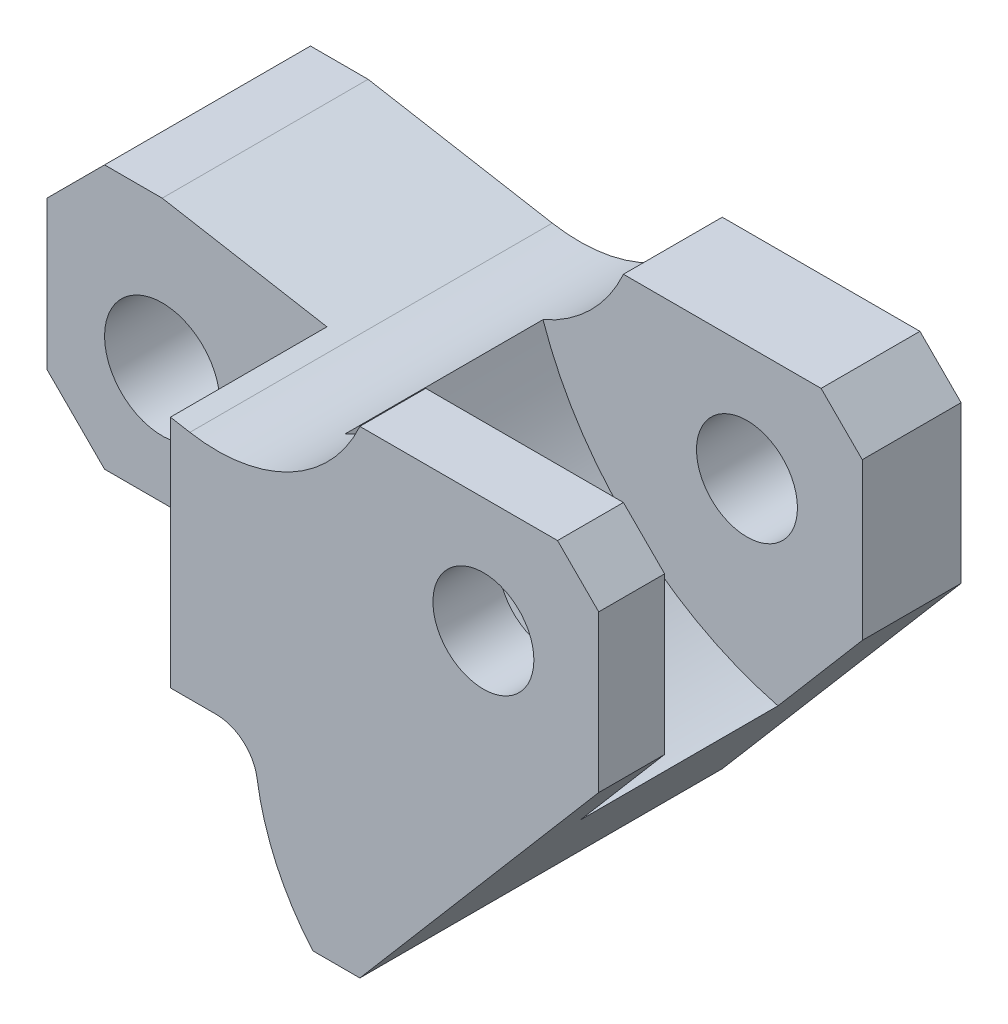
SolidWorks part; units mm, degrees
material "AISI 1020"
ref_plane "Front Plane" through (0, 0, 0) normal (0, 0, 1) x (1, 0, 0)
ref_plane "Top Plane" through (0, 0, 0) normal (0, 1, 0) x (1, 0, 0)
ref_plane "Right Plane" through (0, 0, 0) normal (1, 0, 0) x (0, 0, -1)
sketch "Sketch4" plane through (0, 0, 0) normal (0, 0, 1) x (1, 0, 0)
  line L0 (-153.4752, 21.7594) -> (-153.4752, 53.7594)
  line L1 (-153.4752, 53.7594) -> (-139.4752, 53.7594)
  line L2 (-139.4752, 53.7594) -> (-117.1138, 49.8164)
  line L3 (-96.4752, 60.7594) -> (-67.4752, 60.7594)
  line L4 (-67.4752, 60.7594) -> (-67.4752, 36.7594)
  line L5 (-67.4752, 36.7594) -> (-96.4752, 2.7594)
  line L6 (-96.4752, 2.7594) -> (-102.1782, 2.7594)
  line L7 (-153.4752, 21.7594) -> (-113.8997, 21.7594)
  arc A0 (-117.1138, 49.8164) -> (-96.4752, 60.7594) centre (-113.8145, 68.5278) ccw
  arc A1 (-102.1782, 2.7594) -> (-108.954, 17.4947) centre (-80.2693, 21.7594) cw construction
  arc A2 (-108.954, 17.4947) -> (-113.8997, 21.7594) centre (-113.8997, 16.7594) ccw construction
  arc A3 (-113.8997, 21.7594) -> (-108.954, 17.4947) centre (-113.8997, 16.7594) cw
  arc A4 (-108.954, 17.4947) -> (-102.1782, 2.7594) centre (-80.2693, 21.7594) ccw
  dimension "D4" = 19
  dimension "D9" = 29
  dimension "D10" = 5
  dimension "D1" = 32
  dimension "D2" = 14
  dimension "D3" = 10
  dimension "D5" = 29
  dimension "D6" = 24
  dimension "D7" = 29
  dimension "D8" = 58
  dimension "D11" = 19
  dimension "D12" = 86
  dimension "D13" = 19
extrude "Boss-Extrude1" add sketch "Sketch4" along normal blind 44
sketch "Sketch5" plane through (0, 0, 0) normal (0, 0, 1) x (1, 0, 0)
  line L0 (-153.4752, 53.7594) -> (-153.4752, 21.7594) construction
  line L1 (-153.4752, 21.7594) -> (-113.8997, 21.7594) construction
  circle A0 centre (-139.4752, 35.7594) radius 7
  dimension "D1" = 14
  dimension "D2" = 14
extrude "Cut-Extrude1" cut sketch "Sketch5" along normal through all
chamfer "Chamfer1" distance 7 angle 45 1 edges at (-153.4752, 53.7594, 22)
chamfer "Chamfer2" distance 7 angle 45 1 edges at (-153.4752, 21.7594, 22)
chamfer "Chamfer3" distance 5 angle 45 1 edges at (-67.4752, 60.7594, 22)
sketch "Sketch8" plane through (0, 0, 44) normal (0, 0, 1) x (1, 0, 0)
  line L0 (-67.4752, 36.7594) -> (-67.4752, 55.7594) construction
  line L1 (-72.4752, 60.7594) -> (-96.4752, 60.7594) construction
  circle A0 centre (-81.4752, 46.7594) radius 6.1286
  dimension "D1" = 14
  dimension "D2" = 14
extrude "Cut-Extrude2" cut sketch "Sketch8" against normal through all
sketch "Sketch9" plane through (0, 53.7594, 0) normal (0, 1, 0) x (1, 0, 0)
  line L1 (-153.4752, -44) -> (-119.4752, -44)
  line L2 (-153.4752, -44) -> (-153.4752, -25)
  line L3 (-153.4752, -25) -> (-119.4752, -25)
  line L4 (-119.4752, -44) -> (-119.4752, -25)
  dimension "D1" = 19
  dimension "D2" = 52
extrude "Cut-Extrude3" cut sketch "Sketch9" against normal through all
sketch "Sketch10" plane through (0, 0, 0) normal (0, 0, -1) x (-1, 0, 0)
  line L0 (96.4752, 2.7594) -> (67.4752, 36.7594) construction
  line L1 (67.4752, 36.7594) -> (67.4752, 55.7594) construction
  line L2 (72.4752, 60.7594) -> (96.4752, 60.7594) construction
  line L3 (77.7105, 24.7594) -> (67.4752, 36.7594)
  line L4 (67.4752, 36.7594) -> (67.4752, 55.7594)
  line L5 (67.4752, 55.7594) -> (72.4752, 60.7594)
  line L6 (72.4752, 60.7594) -> (96.4752, 60.7594)
  arc A0 (106.2383, 51.1037) -> (77.7105, 24.7594) centre (67.4752, 64.4612) cw
  arc A1 (96.4752, 60.7594) -> (117.1138, 49.8164) centre (113.8145, 68.5278) ccw construction
  arc A2 (96.4752, 60.7594) -> (106.2383, 51.1037) centre (113.8145, 68.5278) ccw
  dimension "D1" = 41
  dimension "D2" = 36
extrude "Cut-Extrude4" cut sketch "Sketch10" against normal blind 24 from offset 12
